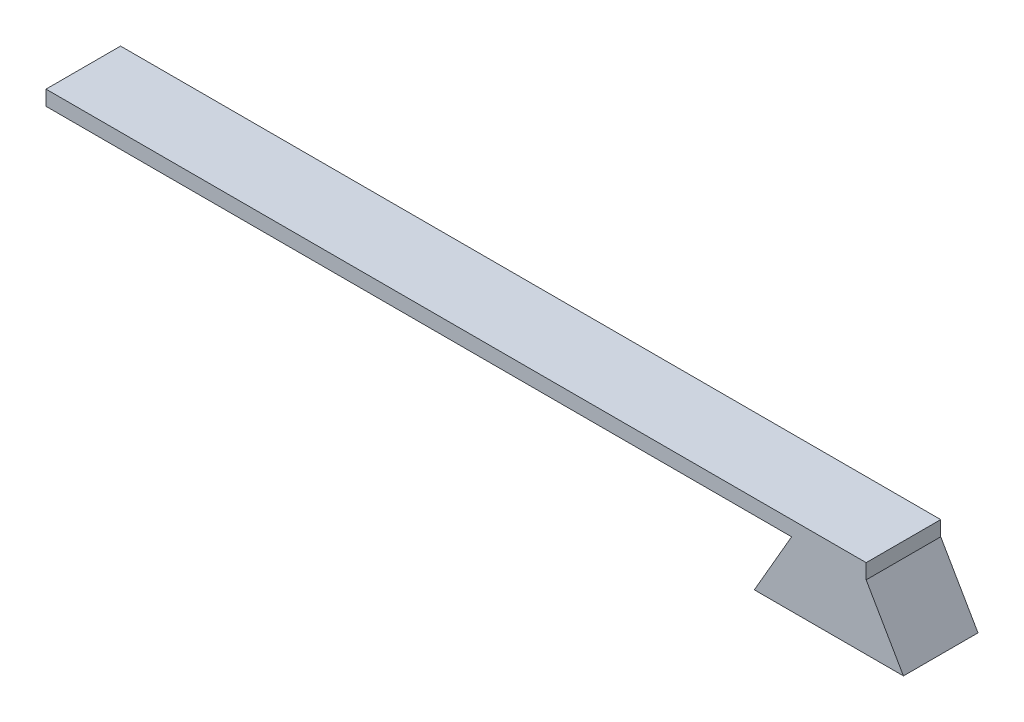
SolidWorks part; units mm, degrees
ref_plane "Alzado" through (0, 0, 0) normal (0, 0, 1) x (1, 0, 0)
ref_plane "Planta" through (0, 0, 0) normal (0, 1, 0) x (1, 0, 0)
ref_plane "Vista lateral" through (0, 0, 0) normal (1, 0, 0) x (0, 0, -1)
sketch "Croquis1" plane through (0, 0, 0) normal (0, 0, 1) x (1, 0, 0)
  line L0 (0, 0) -> (50, 86.6025)
  line L1 (50, 86.6025) -> (150, 86.6025)
  line L2 (150, 86.6025) -> (200, 0)
  line L3 (200, 0) -> (0, 0)
  dimension "D1" = 200
  dimension "D2" = 100
  dimension "D3" = 60
  dimension "D4" = 60
extrude "Saliente-Extruir1" add sketch "Croquis1" along normal blind 100
sketch "Croquis2" plane through (0, 86.6025, 0) normal (0, 1, 0) x (1, 0, 0)
  line L0 (150, -100) -> (150, 0) construction
  line L1 (50, 0) -> (150, 0)
  line L2 (50, 0) -> (50, -100)
  line L3 (50, -100) -> (150, -100)
  line L4 (150, 0) -> (150, -100)
extrude "Saliente-Extruir2" add sketch "Croquis2" along normal blind 20
sketch "Croquis3" plane through (50, 0, 0) normal (-1, 0, 0) x (0, 0, 1)
  line L1 (0, 106.6025) -> (100, 106.6025)
  line L2 (0, 106.6025) -> (0, 86.6025)
  line L3 (0, 86.6025) -> (100, 86.6025)
  line L4 (100, 106.6025) -> (100, 86.6025)
extrude "Saliente-Extruir3" add sketch "Croquis3" along normal blind 1000
